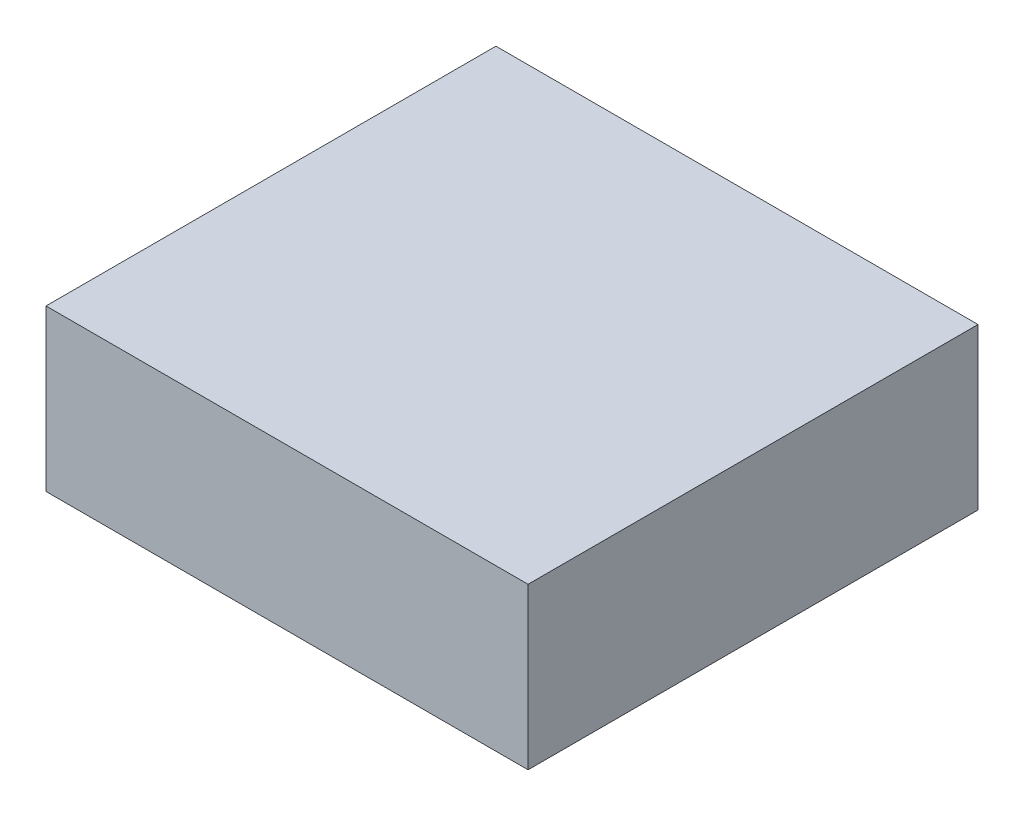
SolidWorks part; units mm, degrees
material "Aleación 1060"
ref_plane "Alzado" through (0, 0, 0) normal (0, 0, 1) x (1, 0, 0)
ref_plane "Planta" through (0, 0, 0) normal (0, 1, 0) x (1, 0, 0)
ref_plane "Vista lateral" through (0, 0, 0) normal (1, 0, 0) x (0, 0, -1)
sketch "Croquis1" plane through (0, 0, 0) normal (0, 1, 0) x (1, 0, 0)
  line L1 (30, -28) -> (-30, -28)
  line L2 (30, -28) -> (30, 28)
  line L3 (30, 28) -> (-30, 28)
  line L4 (-30, -28) -> (-30, 28)
  line L5 (30, -28) -> (-30, 28) construction
  line L6 (30, 28) -> (-30, -28) construction
  point P0 (0, 0)
  dimension "D1" = 56
  dimension "D2" = 60
extrude "Saliente-Extruir1" add sketch "Croquis1" along normal blind 20
